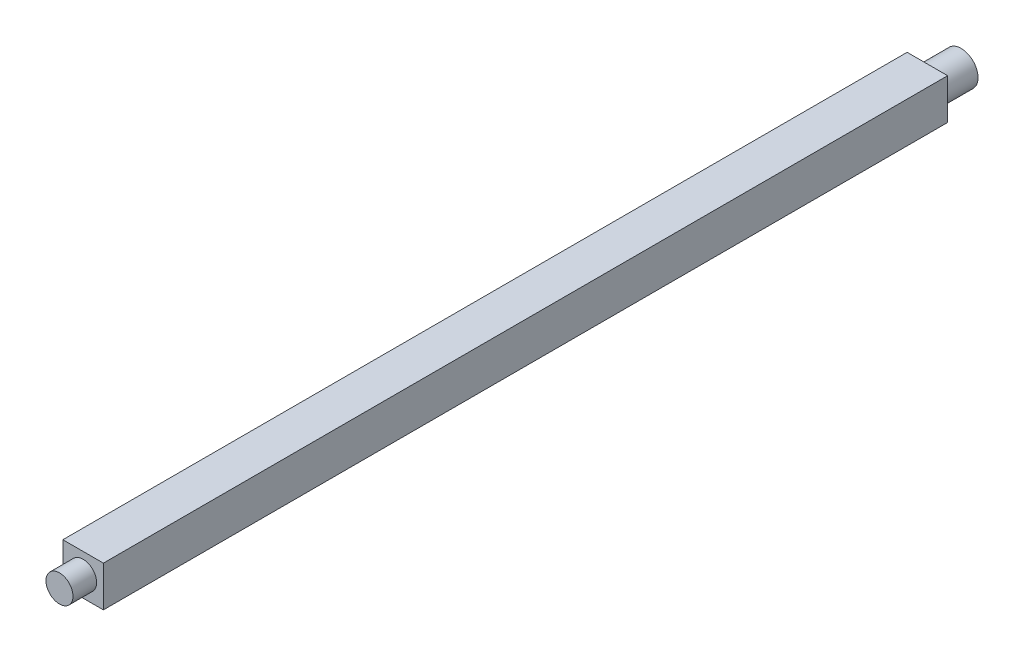
SolidWorks part; units mm, degrees
ref_plane "前视基准面" through (0, 0, 0) normal (0, 0, 1) x (1, 0, 0)
ref_plane "上视基准面" through (0, 0, 0) normal (0, 1, 0) x (1, 0, 0)
ref_plane "右视基准面" through (0, 0, 0) normal (1, 0, 0) x (0, 0, -1)
sketch "草图1" plane through (0, 0, 0) normal (0, 0, 1) x (1, 0, 0)
  line L7 (5, 0) -> (2.5, 4.3301)
  line L8 (2.5, 4.3301) -> (-2.5, 4.3301)
  line L9 (-2.5, 4.3301) -> (-5, 0)
  line L10 (-5, 0) -> (-2.5, -4.3301)
  line L11 (-2.5, -4.3301) -> (2.5, -4.3301)
  line L12 (2.5, -4.3301) -> (5, 0)
  circle A0 centre (0, 0) radius 5 construction
  dimension "D1" = 10
extrude "凸台-拉伸1" add sketch "草图1" along normal blind 250
sketch "草图2" plane through (0, 0, 250) normal (0, 0, 1) x (1, 0, 0)
  circle A0 centre (0, 0) radius 2.5
  dimension "D1" = 5
extrude "凸台-拉伸2" add sketch "草图2" along normal blind 10
sketch "草图3" plane through (0, 0, 0) normal (0, 0, -1) x (-1, 0, 0)
  circle A0 centre (0, 0) radius 5
  dimension "D1" = 10
extrude "凸台-拉伸3" add sketch "草图3" along normal blind 10
sketch "草图4" plane through (0, 0, 260) normal (0, 0, 1) x (1, 0, 0)
  line L0 (0, 5.3594) -> (0, -5.4971) construction
  line L2 (-1, 3.3356) -> (1, 3.3356)
  line L3 (-1, 3.3356) -> (-1, 1.5)
  line L4 (-1, 1.5) -> (1, 1.5)
  line L5 (1, 3.3356) -> (1, 1.5)
  dimension "D1" = 2
  dimension "D2" = 1
  dimension "D3" = 1.5
extrude "切除-拉伸1" cut sketch "草图4" against normal blind 10
sketch "草图6" plane through (0, 0, 260) normal (0, 0, 1) x (1, 0, 0)
  circle A0 centre (0, 0) radius 2.5
extrude "凸台-拉伸5" add sketch "草图6" against normal blind 5
sketch "草图9" plane through (0, 0, -10) normal (0, 0, -1) x (-1, 0, 0)
  circle A0 centre (0, 0) radius 2.5
extrude "凸台-拉伸7" add sketch "草图9" against normal blind 5
sketch "草图10" plane through (0, 0, -10) normal (0, 0, -1) x (-1, 0, 0)
  circle A0 centre (0, 0) radius 2.5
extrude "切除-拉伸3" cut sketch "草图10" against normal blind 3
sketch "草图11" plane through (0, 0, 260) normal (0, 0, 1) x (1, 0, 0)
  circle A0 centre (0, 0) radius 2.5
extrude "切除-拉伸4" cut sketch "草图11" against normal blind 3
sketch "草图12" plane through (0, 0, -10) normal (0, 0, -1) x (-1, 0, 0)
  circle A0 centre (0, 0) radius 5
extrude "凸台-拉伸8" add sketch "草图12" against normal blind 10
sketch "草图14" plane through (0, 0, 250) normal (0, 0, 1) x (1, 0, 0)
  circle A0 centre (0, 0) radius 2.5
extrude "凸台-拉伸10" add sketch "草图14" along normal blind 1
sketch "草图15" plane through (0, 0, 250) normal (0, 0, 1) x (1, 0, 0)
  line L1 (-6, 6) -> (6, 6)
  line L2 (-6, 6) -> (-6, -6)
  line L3 (-6, -6) -> (6, -6)
  line L4 (6, 6) -> (6, -6)
  line L5 (-6, 6) -> (6, -6) construction
  line L6 (-6, -6) -> (6, 6) construction
  point P0 (0, 0)
  dimension "D1" = 12
  dimension "D2" = 12
extrude "凸台-拉伸11" add sketch "草图15" against normal blind 250
sketch "草图16" plane through (0, 0, 257) normal (0, 0, 1) x (1, 0, 0)
  circle A0 centre (0, 0) radius 4
  dimension "D1" = 8
extrude "凸台-拉伸12" add sketch "草图16" against normal blind 20
